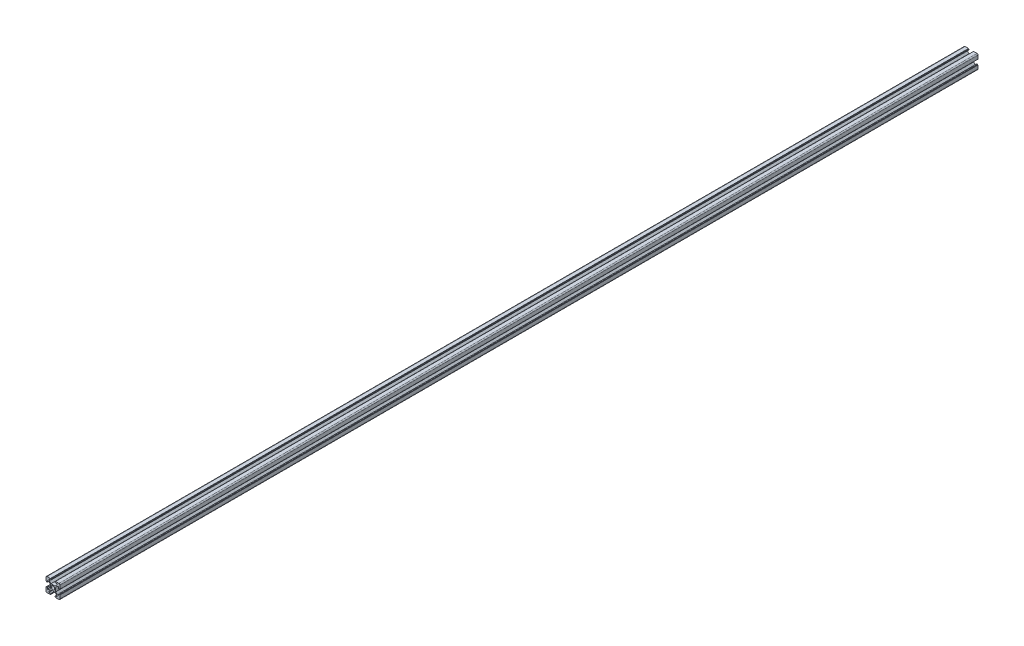
SolidWorks part; units mm, degrees
ref_plane "Front Plane" through (0, 0, 0) normal (0, 0, 1) x (1, 0, 0)
ref_plane "Top Plane" through (0, 0, 0) normal (0, 1, 0) x (1, 0, 0)
ref_plane "Right Plane" through (0, 0, 0) normal (1, 0, 0) x (0, 0, -1)
sketch "Sketch1" plane through (0, 0, 0) normal (0, 0, 1) x (1, 0, 0)
  line L0 (0, 13.3843) -> (0, -12.9126) construction
  line L1 (-14.4653, 0) -> (14.4653, 0) construction
  line L2 (2.8393, 3.9) -> (5.5, 6.5607)
  line L3 (-8.5, 10) -> (-3.6, 10)
  line L4 (-10, 8.5) -> (-10, 3.6)
  line L5 (-8.5, -10) -> (-3.6, -10)
  line L6 (10, 8.5) -> (10, 3.6)
  line L7 (-10, 10) -> (10, -10) construction
  line L8 (-10, -10) -> (10, 10) construction
  line L9 (-5.5, 8.2) -> (-3.1, 8.2)
  line L10 (-5.9626, 4.902) -> (-4.902, 5.9626) construction
  line L11 (-2.8393, 3.9) -> (-5.5, 6.5607)
  line L12 (-5.5, 8.2) -> (-5.5, 6.5607)
  line L13 (-2.8393, 3.9) -> (2.8393, 3.9)
  line L14 (5.5, 8.2) -> (5.5, 6.5607)
  line L15 (-3.1, 9.5) -> (-3.1, 8.2)
  line L16 (3.1, 9.5) -> (3.1, 8.2)
  line L17 (-3.1, 9.5) -> (3.1, 9.5) construction
  line L18 (-3.1, 9.5) -> (-3.6, 9.5)
  line L19 (-3.6, 9.5) -> (-3.6, 10)
  line L20 (3.1, 9.5) -> (3.6, 9.5)
  line L21 (3.6, 9.5) -> (3.6, 10)
  line L22 (3.6, 10) -> (8.5, 10)
  line L23 (3.1, 8.2) -> (5.5, 8.2)
  line L24 (-9.5, -3.1) -> (-9.5, -3.6)
  line L25 (-9.5, -3.6) -> (-10, -3.6)
  line L26 (-9.5, -3.1) -> (-8.2, -3.1)
  line L27 (-8.2, -3.1) -> (-8.2, -5.5)
  line L28 (-8.2, -5.5) -> (-6.5607, -5.5)
  line L29 (-3.9, -2.8393) -> (-6.5607, -5.5)
  line L30 (-3.9, 2.8393) -> (-3.9, -2.8393)
  line L31 (-3.9, 2.8393) -> (-6.5607, 5.5)
  line L32 (-8.2, 5.5) -> (-6.5607, 5.5)
  line L33 (-8.2, 5.5) -> (-8.2, 3.1)
  line L34 (-9.5, 3.1) -> (-8.2, 3.1)
  line L35 (-9.5, 3.1) -> (-9.5, 3.6)
  line L36 (-9.5, 3.6) -> (-10, 3.6)
  line L37 (-3.6, -9.5) -> (-3.6, -10)
  line L38 (-3.1, -9.5) -> (-3.6, -9.5)
  line L39 (-3.1, -9.5) -> (-3.1, -8.2)
  line L40 (-3.1, -8.2) -> (-5.5, -8.2)
  line L41 (-5.5, -8.2) -> (-5.5, -6.5607)
  line L42 (-2.8393, -3.9) -> (-5.5, -6.5607)
  line L43 (2.8393, -3.9) -> (-2.8393, -3.9)
  line L44 (2.8393, -3.9) -> (5.5, -6.5607)
  line L45 (5.5, -8.2) -> (5.5, -6.5607)
  line L46 (5.5, -8.2) -> (3.1, -8.2)
  line L47 (3.1, -9.5) -> (3.6, -9.5)
  line L48 (3.1, -9.5) -> (3.1, -8.2)
  line L49 (3.6, -9.5) -> (3.6, -10)
  line L50 (9.5, -3.6) -> (10, -3.6)
  line L51 (9.5, -3.1) -> (9.5, -3.6)
  line L52 (9.5, -3.1) -> (8.2, -3.1)
  line L53 (8.2, -5.5) -> (8.2, -3.1)
  line L54 (8.2, -5.5) -> (6.5607, -5.5)
  line L55 (3.9, -2.8393) -> (6.5607, -5.5)
  line L56 (3.9, -2.8393) -> (3.9, 2.8393)
  line L57 (3.9, 2.8393) -> (6.5607, 5.5)
  line L58 (8.2, 5.5) -> (6.5607, 5.5)
  line L59 (8.2, 3.1) -> (8.2, 5.5)
  line L60 (9.5, 3.1) -> (8.2, 3.1)
  line L61 (9.5, 3.1) -> (9.5, 3.6)
  line L62 (9.5, 3.6) -> (10, 3.6)
  line L63 (-10, -3.6) -> (-10, -8.5)
  line L64 (3.6, -10) -> (8.5, -10)
  line L65 (10, -3.6) -> (10, -8.5)
  arc A0 (8.5, 10) -> (10, 8.5) centre (8.5, 8.5) cw
  arc A1 (8.5, -10) -> (10, -8.5) centre (8.5, -8.5) ccw
  arc A2 (-10, -8.5) -> (-8.5, -10) centre (-8.5, -8.5) ccw
  arc A3 (-8.5, 10) -> (-10, 8.5) centre (-8.5, 8.5) ccw
  circle A4 centre (0, 0.2358) radius 2.5
  point P5 (0, 0)
  point P30 (-5.4323, 5.4323)
  point P38 (0, 9.5)
  dimension "D3" = 1.5
  dimension "D15" = 5
  dimension "D1" = 20
  dimension "D2" = 20
  dimension "D4" = 6.2
  dimension "D5" = 11
  dimension "D6" = 1.8
  dimension "D7" = 1.5
  dimension "D8" = 90
  dimension "D9" = 0.5
  dimension "D10" = 0.5
  dimension "D11" = 0.5
  dimension "D12" = 0.5
  dimension "D13" = 6.1
  dimension "D14" = 45
extrude "Boss-Extrude1" add sketch "Sketch1" along normal blind 1313
